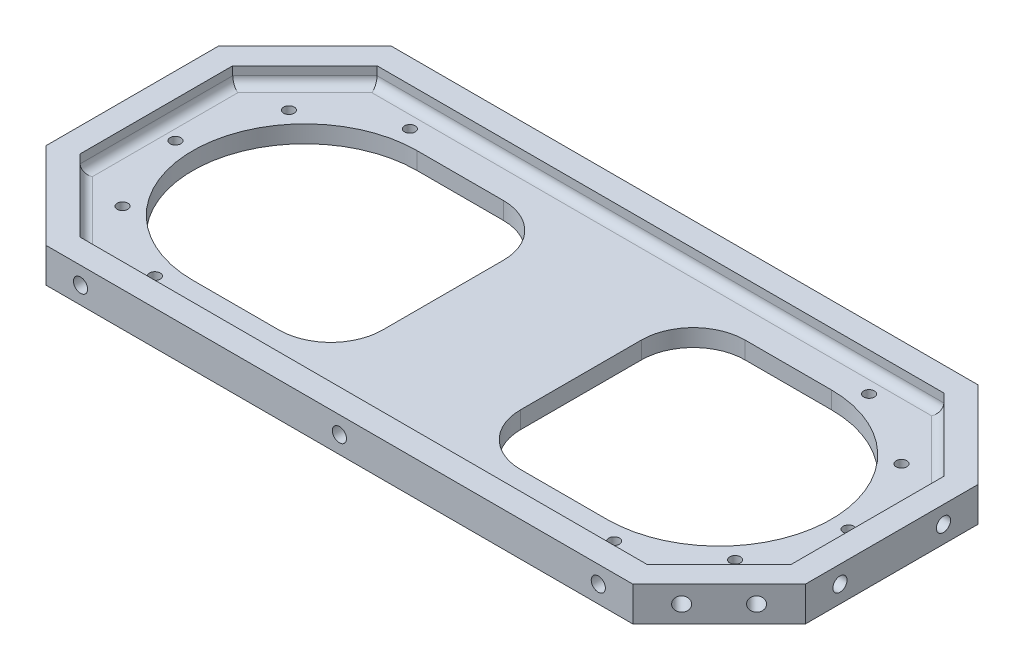
SolidWorks part; units mm, degrees
material "ABS"
ref_plane "Front Plane" through (0, 0, 0) normal (0, 0, 1) x (1, 0, 0)
ref_plane "Top Plane" through (0, 0, 0) normal (0, 1, 0) x (1, 0, 0)
ref_plane "Right Plane" through (0, 0, 0) normal (1, 0, 0) x (0, 0, -1)
sketch "Sketch1" plane through (0, 0, 0) normal (0, 1, 0) x (1, 0, 0)
  line L1 (0, 0) -> (60, 0) construction
  line L3 (60, -75) -> (0, -75) construction
  line L7 (0, 12.5) -> (0, 0)
  line L9 (0, -75) -> (0, -87.5)
  line L10 (0, -115.7193) -> (0, -87.5) construction
  line L11 (0, -75) -> (0, 0)
  line L12 (0, 12.5) -> (85, 12.5)
  line L14 (85, 12.5) -> (110, -12.5)
  line L15 (110, -12.5) -> (110, -62.5)
  line L16 (110, -62.5) -> (85, -87.5)
  line L17 (0, -87.5) -> (85, -87.5)
  line L18 (60, -5) -> (20, -5)
  line L19 (60, -70) -> (20, -70)
  line L20 (20, -5) -> (20, -70)
  arc A0 (60, 0) -> (60, -75) centre (60, -37.5) cw construction
  arc A4 (60, -70) -> (60, -5) centre (60, -37.5) ccw
  dimension "D1" = 75
  dimension "D3" = 120
  dimension "D4" = 135
  dimension "D2" = 5
  dimension "D5" = 135
  dimension "D6" = 220
  dimension "D8" = 100
  dimension "D7" = 25
  dimension "D9" = 40
extrude "Main" add sketch "Sketch1" along normal blind 10
sketch "Sketch3" plane through (0, 10, 0) normal (0, 1, 0) x (1, 0, 0)
  arc A0 (60, -75) -> (60, 0) centre (60, -37.5) ccw construction
  arc A1 (60, -75) -> (60, 0) centre (60, -37.5) ccw construction
  circle A2 centre (97.5, -37.5) radius 1.55
  dimension "D1" = 3.1
extrude "Actuator Screw Hole" cut sketch "Sketch3" against normal through all
pattern_circular "Actuator Screw Hole Pattern" count 3 every 40 about axis through (60, 0, 37.5) along (0, 1, 0) of "Actuator Screw Hole"
fillet "Midspan fillet" radius 15 2 edges at (20, 5, 5) (20, 5, 70)
mirror "Mirror1" about plane through (0, 0, 0) normal (1, 0, 0) of bodies 103
sketch "Sketch7" plane through (0, 10, 0) normal (0, 1, 0) x (1, 0, 0)
  line L0 (0, -6.5) -> (0, -37.5) construction
  line L1 (110, -37.5) -> (-110, -37.5) construction
  line L2 (110, -12.5) -> (110, -62.5) construction
  line L3 (-85, 12.5) -> (85, 12.5) construction
  line L4 (-110, -12.5) -> (-110, -62.5) construction
  line L5 (0, -37.5) -> (0, -68.5) construction
  circle A0 centre (0, -68.5) radius 12
  circle A1 centre (0, -6.5) radius 12
  dimension "D1" = 24
  dimension "D2" = 7
extrude "Wire holes" [suppressed] cut sketch "Sketch7" against normal through all
sketch "Sketch8" plane through (0, 10, 0) normal (0, 1, 0) x (1, 0, 0)
  line L16 (82.1005, 5.5) -> (-82.1005, 5.5)
  line L17 (-82.1005, 5.5) -> (-103, -15.3995)
  line L18 (-103, -15.3995) -> (-103, -59.6005)
  line L19 (-103, -59.6005) -> (-82.1005, -80.5)
  line L20 (-82.1005, -80.5) -> (82.1005, -80.5)
  line L21 (82.1005, -80.5) -> (103, -59.6005)
  line L22 (103, -59.6005) -> (103, -15.3995)
  line L23 (103, -15.3995) -> (82.1005, 5.5)
  line L24 (82.1005, 5.5) -> (-82.1005, 5.5)
  line L25 (-82.1005, 5.5) -> (-103, -15.3995)
  line L26 (-103, -15.3995) -> (-103, -59.6005)
  line L27 (-103, -59.6005) -> (-82.1005, -80.5)
  line L28 (-82.1005, -80.5) -> (82.1005, -80.5)
  line L29 (82.1005, -80.5) -> (103, -59.6005)
  line L30 (103, -59.6005) -> (103, -15.3995)
  line L31 (103, -15.3995) -> (82.1005, 5.5)
  dimension "D1" = 7
extrude "Dish" cut sketch "Sketch8" against normal blind 5
fillet "Dish fillet" radius 2.5 8 edges at (0, 5, 80.5) (0, 5, -5.5) (92.5503, 5, 4.9497) (103, 5, 37.5) (92.5503, 5, 70.0503) (-92.5503, 5, 70.0503) (-103, 5, 37.5) (-92.5503, 5, 4.9497)
chamfer "Wire hole chamfer" [suppressed] distance 1 angle 45
sketch3d "3DSketch2"
  line L0 (-85, 5, 87.5) -> (-75, 5, 87.5) construction
  line L1 (-85, 10, 87.5) -> (-85, 0, 87.5) construction
  line L2 (-75, 5, 87.5) -> (0, 5, 87.5) construction
  line L3 (0, 5, 87.5) -> (75, 5, 87.5) construction
  line L4 (75, 5, 87.5) -> (85, 5, 87.5) construction
  line L5 (85, 10, 87.5) -> (85, 0, 87.5) construction
  line L6 (85, 5, 87.5) -> (92.0711, 5, 80.4289) construction
  line L7 (92.0711, 5, 80.4289) -> (102.9289, 5, 69.5711) construction
  line L8 (102.9289, 5, 69.5711) -> (110, 5, 62.5) construction
  line L9 (110, 10, 62.5) -> (110, 0, 62.5) construction
  line L10 (110, 5, 62.5) -> (110, 5, 52.5) construction
  line L11 (110, 5, 52.5) -> (110, 5, 22.5) construction
  line L12 (110, 5, 22.5) -> (110, 5, 12.5) construction
  line L13 (110, 10, 12.5) -> (110, 0, 12.5) construction
  line L14 (110, 5, 12.5) -> (102.9289, 5, 5.4289) construction
  line L15 (102.9289, 5, 5.4289) -> (92.0711, 5, -5.4289) construction
  line L16 (92.0711, 5, -5.4289) -> (85, 5, -12.5) construction
  line L17 (85, 10, -12.5) -> (85, 0, -12.5) construction
  line L18 (85, 5, -12.5) -> (75, 5, -12.5) construction
  line L19 (75, 5, -12.5) -> (0, 5, -12.5) construction
  line L20 (-75, 5, -12.5) -> (-85, 5, -12.5) construction
  line L21 (-85, 10, -12.5) -> (-85, 0, -12.5) construction
  line L22 (-85, 5, -12.5) -> (-92.0711, 5, -5.4289) construction
  line L23 (-92.0711, 5, -5.4289) -> (-102.9289, 5, 5.4289) construction
  line L24 (-102.9289, 5, 5.4289) -> (-110, 5, 12.5) construction
  line L25 (-110, 10, 12.5) -> (-110, 0, 12.5) construction
  line L26 (-110, 5, 12.5) -> (-110, 5, 22.5) construction
  line L27 (-110, 5, 22.5) -> (-110, 5, 52.5) construction
  line L28 (-110, 5, 52.5) -> (-110, 5, 62.5) construction
  line L29 (-110, 10, 62.5) -> (-110, 0, 62.5) construction
  line L30 (-110, 5, 62.5) -> (-102.9289, 5, 69.5711) construction
  line L31 (-102.9289, 5, 69.5711) -> (-92.0711, 5, 80.4289) construction
  line L32 (-92.0711, 5, 80.4289) -> (-85, 5, 87.5) construction
  line L33 (0, 5, -12.5) -> (-75, 5, -12.5) construction
  dimension "D1" = 10
  dimension "D2" = 10
  dimension "D3" = 10
hole_wizard "Ø4.0mm Dowel Hole1" positions "3DSketch5" profile "Sketch12" hole size "Ø4.0" standard "ANSI Metric"
sketch3d "3DSketch5"
  line L0 (85, 5, -12.5) -> (75, 5, -12.5) construction
  line L1 (85, 10, -12.5) -> (85, 0, -12.5) construction
  line L2 (75, 5, -12.5) -> (0, 5, -12.5) construction
  line L3 (0, 5, -12.5) -> (-75, 5, -12.5) construction
  line L4 (-75, 5, -12.5) -> (-85, 5, -12.5) construction
  line L5 (-85, 10, -12.5) -> (-85, 0, -12.5) construction
  line L6 (-85, 5, -12.5) -> (-92.0711, 5, -5.4289) construction
  line L7 (-92.0711, 5, -5.4289) -> (-102.9289, 5, 5.4289) construction
  line L8 (-102.9289, 5, 5.4289) -> (-110, 5, 12.5) construction
  line L9 (-110, 10, 12.5) -> (-110, 0, 12.5) construction
  line L10 (-110, 5, 12.5) -> (-110, 5, 22.5) construction
  line L11 (-110, 5, 22.5) -> (-110, 5, 52.5) construction
  line L12 (-110, 5, 52.5) -> (-110, 5, 62.5) construction
  line L13 (-110, 10, 62.5) -> (-110, 0, 62.5) construction
  line L14 (-110, 5, 62.5) -> (-102.9289, 5, 69.5711) construction
  line L15 (-102.9289, 5, 69.5711) -> (-92.0711, 5, 80.4289) construction
  line L16 (-92.0711, 5, 80.4289) -> (-85, 5, 87.5) construction
  line L17 (-85, 10, 87.5) -> (-85, 0, 87.5) construction
  line L18 (-85, 5, 87.5) -> (-75, 5, 87.5) construction
  line L19 (-75, 5, 87.5) -> (0, 5, 87.5) construction
  line L20 (0, 5, 87.5) -> (75, 5, 87.5) construction
  line L21 (75, 5, 87.5) -> (85, 5, 87.5) construction
  line L22 (85, 10, 87.5) -> (85, 0, 87.5) construction
  line L23 (85, 5, 87.5) -> (92.0711, 5, 80.4289) construction
  line L24 (92.0711, 5, 80.4289) -> (102.9289, 5, 69.5711) construction
  line L25 (102.9289, 5, 69.5711) -> (110, 5, 62.5) construction
  line L26 (110, 10, 62.5) -> (110, 0, 62.5) construction
  line L27 (110, 5, 62.5) -> (110, 5, 52.5) construction
  line L28 (110, 5, 52.5) -> (110, 5, 22.5) construction
  line L29 (110, 5, 22.5) -> (110, 5, 12.5) construction
  line L30 (110, 10, 12.5) -> (110, 0, 12.5) construction
  line L31 (110, 5, 12.5) -> (102.9289, 5, 5.4289) construction
  line L32 (102.9289, 5, 5.4289) -> (92.0711, 5, -5.4289) construction
  line L33 (92.0711, 5, -5.4289) -> (85, 5, -12.5) construction
  line L34 (110, 5, 12.5) -> (85, 5, -12.5) construction
  line L36 (-85, 5, -12.5) -> (-110, 5, 12.5) construction
  line L38 (-110, 5, 62.5) -> (-85, 5, 87.5) construction
  line L40 (85, 5, 87.5) -> (110, 5, 62.5) construction
  point P0 (75, 5, -12.5)
  point P2 (0, 5, -12.5)
  point P4 (-75, 5, -12.5)
  point P6 (-92.0711, 5, -5.4289)
  point P8 (-102.9289, 5, 5.4289)
  point P10 (-110, 5, 22.5)
  point P12 (-110, 5, 52.5)
  point P14 (-102.9289, 5, 69.5711)
  point P16 (-92.0711, 5, 80.4289)
  point P18 (-75, 5, 87.5)
  point P20 (0, 5, 87.5)
  point P22 (75, 5, 87.5)
  point P24 (92.0711, 5, 80.4289)
  point P26 (102.9289, 5, 69.5711)
  point P28 (110, 5, 52.5)
  point P30 (110, 5, 22.5)
  point P32 (102.9289, 5, 5.4289)
  point P34 (92.0711, 5, -5.4289)
  dimension "D1" = 10
  dimension "D2" = 10
  dimension "D3" = 10
sketch "Sketch12" plane through (75, 5, -12.5) normal (1, 0, 0) x (0, 1, 0)
  line L0 (0, 0) -> (0, 5.7)
  line L1 (0, 5.7) -> (2.05, 5.7)
  line L2 (2.05, 5.7) -> (2.05, 0)
  line L5 (2.05, 0) -> (0, 0)
  line L10 (0, 5.7) -> (-2.05, 5.7) construction
  line L11 (0, -6.35) -> (0, 107.95) construction
  dimension "Hole Dia." = 4.1
  dimension "Hole Depth" = 5.7
  dimension "Drill Angle" = 180
equation "\"length\" = 215mm"
equation "\"width\" = 220mm"
equation "\"height\" = 100mm"
equation "\"skin_th\" = 8mm"
equation "\"D6@Sketch1\"=\"width\""
equation "\"D8@Sketch1\"=\"height\""
